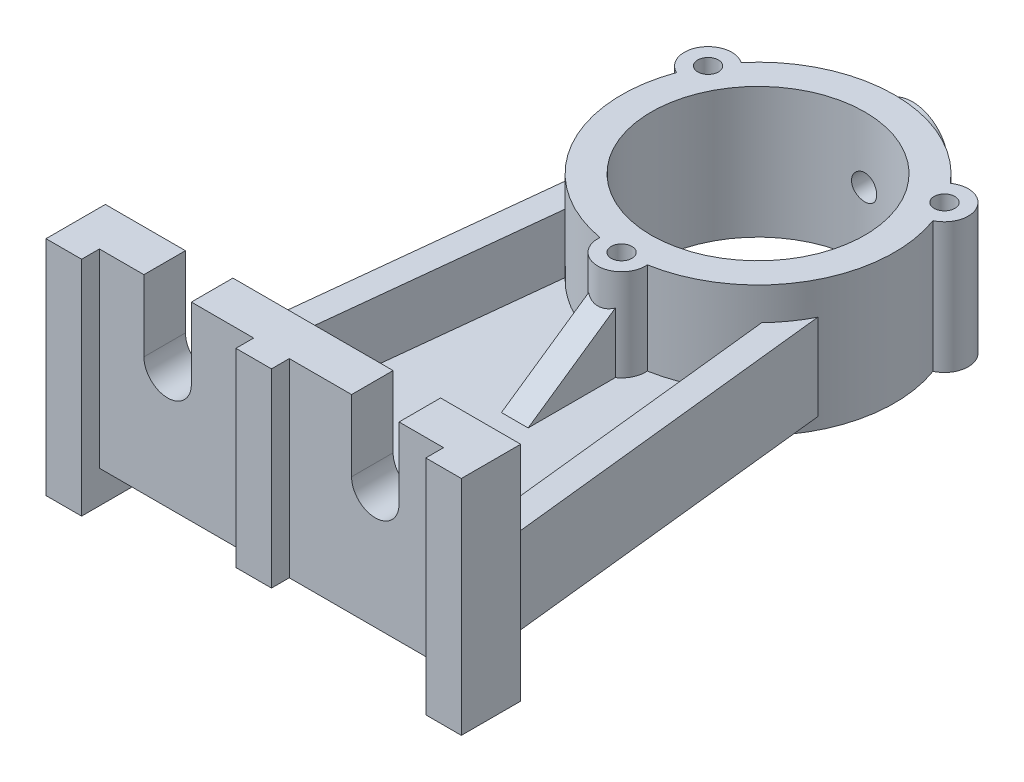
SolidWorks part; units mm, degrees
ref_plane "前视基准面" through (0, 0, 0) normal (0, 0, 1) x (1, 0, 0)
ref_plane "上视基准面" through (0, 0, 0) normal (0, 1, 0) x (1, 0, 0)
ref_plane "右视基准面" through (0, 0, 0) normal (1, 0, 0) x (0, 0, -1)
sketch "草图1" plane through (0, 0, 0) normal (0, 1, 0) x (1, 0, 0)
  circle A0 centre (0, 0) radius 46
  dimension "D1" = 92
extrude "凸台-拉伸1" add sketch "草图1" along normal blind 44
sketch "草图2" plane through (0, 44, 0) normal (0, 1, 0) x (1, 0, 0)
  circle A0 centre (0, -46) radius 8
  circle A1 centre (0, 0) radius 46 construction
  dimension "D1" = 16
extrude "凸台-拉伸2" add sketch "草图2" against normal blind 44
sketch "草图3" plane through (0, 44, 0) normal (0, 1, 0) x (1, 0, 0)
  circle A0 centre (0, -46) radius 3.5
  arc A1 (-7.9697, -45.3043) -> (7.9697, -45.3043) centre (0, -46) ccw construction
  dimension "D1" = 7
extrude "切除-拉伸1" cut sketch "草图3" against normal blind 44
pattern_circular "阵列(圆周)1" count 3 over 360 about axis through (0, 0, 0) along (0, 1, 0) of "凸台-拉伸2", "切除-拉伸1"
sketch "草图5" plane through (0, 0, 0) normal (0, 0, 1) x (1, 0, 0)
  line L0 (0, 0) -> (0, 27) construction
  line L1 (-12, 0) -> (-12, 27)
  line L2 (12, 0) -> (12, 27)
  line L3 (-12, 0) -> (12, 0)
  arc A1 (12, 27) -> (-12, 27) centre (0, 27) ccw
  point P3 (0, 13.5)
  dimension "D1" = 12
  dimension "D2" = 27
extrude "凸台-拉伸3" add sketch "草图5" along normal blind 44 from offset 52 offset against normal yes
sketch "草图6" plane through (0, 44, 0) normal (0, 1, 0) x (1, 0, 0)
  circle A0 centre (0, 0) radius 36
  dimension "D1" = 72
extrude "切除-拉伸2" cut sketch "草图6" against normal blind 44
sketch "草图7" plane through (0, 0, -52) normal (0, 0, -1) x (-1, 0, 0)
  point P0 (0, 22)
  dimension "D1" = 22
hole_wizard "M10 螺纹孔1" positions "草图7" profile "草图8" tap size "M10" standard "GB"
sketch "草图8" plane through (0, 22, -52) normal (1, 0, 0) x (0, 1, 0)
  line L0 (0, 0) -> (0, 16)
  line L1 (0, 16) -> (4.25, 16)
  line L2 (4.25, 16) -> (4.25, 0)
  line L5 (4.25, 0) -> (0, 0)
  line L11 (0, -6.35) -> (0, 107.95) construction
  dimension "通孔螺纹孔钻头直径" = 8.5
  dimension "通孔螺纹孔钻头深度" = 16
cosmetic thread "孔螺纹线1" parameters "D2"=10
sketch "草图9" plane through (0, 0, 0) normal (0, 1, 0) x (1, 0, 0)
  line L0 (0, 0) -> (0, -172.8084) construction
  line L1 (-41, -20.8567) -> (-55, -150)
  line L2 (41, -20.8567) -> (55, -150)
  line L3 (-55, -150) -> (55, -150)
  arc A0 (-43.2196, 15.7502) -> (-7.9697, -45.3043) centre (0, 0) ccw construction
  arc A1 (-7.9697, -45.3043) -> (7.9697, -45.3043) centre (0, -46) ccw construction
  arc A2 (7.9697, -45.3043) -> (43.2196, 15.7502) centre (0, 0) ccw construction
  arc A3 (-41, -20.8567) -> (-7.9697, -45.3043) centre (0, 0) ccw
  arc A4 (-7.9697, -45.3043) -> (7.9697, -45.3043) centre (0, -46) ccw
  arc A5 (7.9697, -45.3043) -> (41, -20.8567) centre (0, 0) ccw
  dimension "D1" = 82
  dimension "D2" = 110
  dimension "D3" = 150
extrude "凸台-拉伸4" add sketch "草图9" along normal blind 9 from offset 4
sketch "草图10" plane through (0, 13, 0) normal (0, 1, 0) x (1, 0, 0)
  line L10 (45.9473, -150) -> (33.1442, -31.8977)
  line L11 (-33.1442, -31.8977) -> (-45.9473, -150)
  line L12 (-32.0524, -21.8266) -> (-46.0524, -150.97) construction
  line L13 (-41, -20.8567) -> (-55, -150)
  line L14 (-55, -150) -> (55, -150)
  line L15 (55, -150) -> (41, -20.8567)
  line L16 (-41, -20.8567) -> (-55, -150)
  line L17 (-55, -150) -> (-45.9473, -150)
  line L18 (55, -150) -> (41, -20.8567)
  line L19 (46.0524, -150.97) -> (32.0524, -21.8266) construction
  line L20 (45.9473, -150) -> (55, -150)
  arc A3 (-41, -20.8567) -> (-7.9697, -45.3043) centre (0, 0) ccw
  arc A4 (7.9697, -45.3043) -> (41, -20.8567) centre (0, 0) ccw
  arc A5 (-7.9697, -45.3043) -> (7.9697, -45.3043) centre (0, -46) ccw
  arc A6 (-41, -20.8567) -> (-33.1442, -31.8977) centre (0, 0) ccw
  arc A7 (33.1442, -31.8977) -> (41, -20.8567) centre (0, 0) ccw
  dimension "D1" = 0
  dimension "D2" = 9
extrude "凸台-拉伸5" add sketch "草图10" along normal blind 20
sketch "草图11" plane through (0, 0, 0) normal (1, 0, 0) x (0, 0, -1)
  line L0 (-53.0338, 33) -> (-82, 13)
  line L2 (-150, 13) -> (-31.8977, 13) construction
  line L5 (-150, 33) -> (-31.8977, 33) construction
  point P2 (-54, 44)
  point P3 (-58.0188, 33)
  point P4 (-106.1872, 13)
  point P8 (-60.2735, 44)
  point P11 (-53.0338, 33)
  dimension "D1" = 82
rib "筋1" sketch "草图11" sketch "草图11" thickness 9 extrusion direction parallel to sketch draft on no parameters "D1"=9
sketch "草图13" plane through (0, 0, 0) normal (0, 0, 1) x (1, 0, 0)
  line L0 (0, 0) -> (0, 52.947) construction
  line L1 (-70, 75) -> (70, 75)
  line L2 (-70, 75) -> (-70, 11)
  line L3 (-70, 11) -> (70, 11)
  line L4 (70, 75) -> (70, 11)
  dimension "D1" = 140
  dimension "D2" = 11
  dimension "D3" = 64
extrude "凸台-拉伸6" add sketch "草图13" against normal blind 20 from offset 170
sketch "草图14" plane through (0, 0, 150) normal (0, 0, -1) x (-1, 0, 0)
  line L0 (35, 75) -> (35, 51) construction
  line L1 (-70, 75) -> (70, 75) construction
  line L2 (43, 75) -> (43, 51)
  line L3 (27, 75) -> (27, 51)
  arc A0 (43, 75) -> (27, 75) centre (35, 75) ccw
  arc A1 (27, 51) -> (43, 51) centre (35, 51) ccw
  point P4 (35, 63)
  dimension "D3" = 8
  dimension "D1" = 35
  dimension "D2" = 24
extrude "切除-拉伸3" cut sketch "草图14" against normal through all
mirror "镜向1" about plane through (0, 0, 0) normal (1, 0, 0) of "切除-拉伸3"
sketch "草图15" plane through (0, 75, 0) normal (0, 1, 0) x (1, 0, 0)
  line L0 (-43, -170) -> (-70, -170) construction
  line L1 (-58, -170) -> (-6, -170)
  line L2 (-58, -170) -> (-58, -164)
  line L3 (-58, -164) -> (-6, -164)
  line L4 (-6, -170) -> (-6, -164)
  line L5 (0, -114.6687) -> (0, -192.2093) construction
  line L6 (-45.9473, -150) -> (45.9473, -150) construction
  dimension "D1" = 116
  dimension "D2" = 12
  dimension "D3" = 14
extrude "切除-拉伸4" cut sketch "草图15" against normal through all
mirror "镜向2" about plane through (0, 0, 0) normal (1, 0, 0) of "切除-拉伸4"
sketch "草图17" plane through (0, 11, 0) normal (0, -1, 0) x (1, 0, 0)
  line L1 (-58, 170) -> (-70, 170)
  line L2 (-58, 170) -> (-58, 150)
  line L3 (-58, 150) -> (-70, 150)
  line L4 (-70, 170) -> (-70, 150)
extrude "凸台-拉伸7" add sketch "草图17" along normal blind 11
mirror "镜向3" about plane through (0, 0, 0) normal (1, 0, 0) of "凸台-拉伸7"
